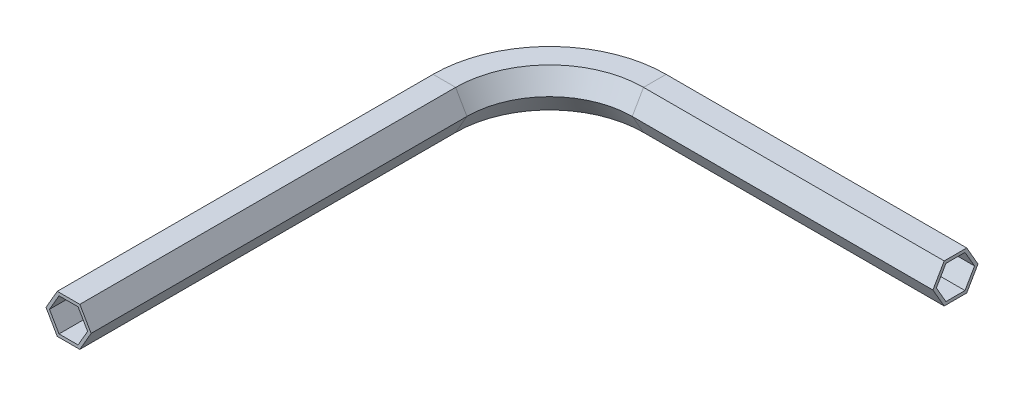
SolidWorks part; units mm, degrees
ref_plane "Plan de face" through (0, 0, 0) normal (0, 0, 1) x (1, 0, 0)
ref_plane "Plan de dessus" through (0, 0, 0) normal (0, 1, 0) x (1, 0, 0)
ref_plane "Plan de droite" through (0, 0, 0) normal (1, 0, 0) x (0, 0, -1)
sketch "Esquisse2" plane through (0, 0, 0) normal (0, 0, 1) x (1, 0, 0)
  line L1 (75, 129.9038) -> (-75, 129.9038)
  line L2 (-75, 129.9038) -> (-150, 0)
  line L3 (-150, 0) -> (-75, -129.9038)
  line L4 (-75, -129.9038) -> (75, -129.9038)
  line L5 (75, -129.9038) -> (150, 0)
  line L6 (150, 0) -> (75, 129.9038)
  circle A0 centre (0, 0) radius 129.9038 construction
  dimension "D1" = 150
sketch "Esquisse3" plane through (0, 0, 0) normal (0, 1, 0) x (1, 0, 0)
  line L0 (0, 0) -> (0, 2500)
  line L1 (700, 3200) -> (2700, 3200)
  arc A0 (0, 2500) -> (700, 3200) centre (700, 2500) cw
  dimension "D2" = 700
  dimension "D1" = 2000
  dimension "D3" = 2500
sweep "Balayage1" add profiles "Esquisse2" path "Esquisse3"
sketch "Esquisse4" plane through (0, 0, 0) normal (0, 0, 1) x (1, 0, 0)
  line L12 (126.906, 0) -> (63.453, 109.9038)
  line L13 (63.453, 109.9038) -> (-63.453, 109.9038)
  line L14 (-63.453, 109.9038) -> (-126.906, 0)
  line L15 (-126.906, 0) -> (-63.453, -109.9038)
  line L16 (-63.453, -109.9038) -> (63.453, -109.9038)
  line L17 (63.453, -109.9038) -> (126.906, 0)
  line L18 (126.906, 0) -> (63.453, 109.9038)
  line L19 (63.453, 109.9038) -> (-63.453, 109.9038)
  line L20 (-63.453, 109.9038) -> (-126.906, 0)
  line L21 (-126.906, 0) -> (-63.453, -109.9038)
  line L22 (-63.453, -109.9038) -> (63.453, -109.9038)
  line L23 (63.453, -109.9038) -> (126.906, 0)
  dimension "D1" = 20
sketch "Esquisse5" plane through (0, 129.9038, 0) normal (0, 1, 0) x (1, 0, 0)
  line L0 (150, 0) -> (150, 2500) construction
  line L1 (150, 0) -> (150, 2500)
  line L2 (700, 3050) -> (2700, 3050) construction
  line L3 (700, 3050) -> (2700, 3050)
  arc A0 (700, 3050) -> (150, 2500) centre (700, 2500) ccw construction
  arc A1 (700, 3050) -> (150, 2500) centre (700, 2500) ccw
sweep "Enlèvement de matière-Balayage1" cut profiles "Esquisse4" path "Esquisse5"
